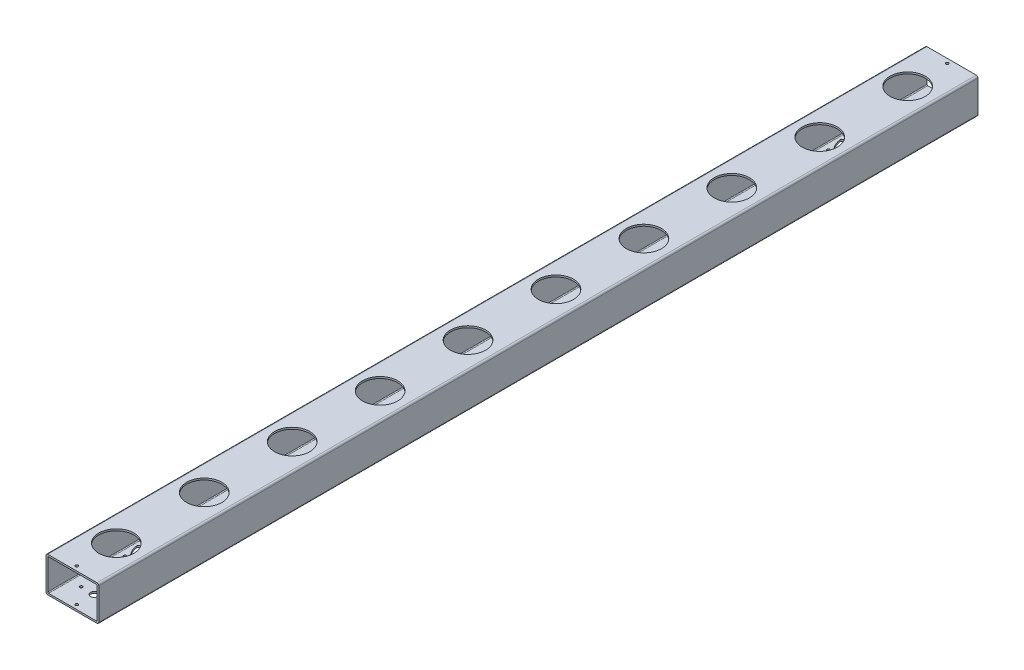
SolidWorks part; units mm, degrees
ref_plane "Plan de face" through (0, 0, 0) normal (0, 0, 1) x (1, 0, 0)
ref_plane "Plan de dessus" through (0, 0, 0) normal (0, 1, 0) x (1, 0, 0)
ref_plane "Plan de droite" through (0, 0, 0) normal (1, 0, 0) x (0, 0, -1)
sketch "Esquisse1" plane through (0, 0, 0) normal (0, 0, 1) x (1, 0, 0)
  line L0 (2, 2) -> (58, 2)
  line L1 (0, 0) -> (60, 0)
  line L2 (0, 0) -> (0, 40)
  line L3 (0, 40) -> (60, 40)
  line L4 (60, 0) -> (60, 40)
  line L5 (58, 2) -> (58, 38)
  line L6 (2, 38) -> (58, 38)
  line L7 (2, 2) -> (2, 38)
  dimension "D1" = 60
  dimension "D2" = 40
  dimension "D3" = 2
extrude "Boss.-Extru.1" add sketch "Esquisse1" along normal blind 1000
fillet "Congé1" radius 1 4 edges at (58, 2, 500) (58, 38, 500) (2, 38, 500) (2, 2, 500)
fillet "Congé2" radius 2 4 edges at (60, 0, 500) (0, 0, 500) (60, 40, 500) (0, 40, 500)
sketch "Esquisse2" plane through (0, 40, 0) normal (0, 1, 0) x (1, 0, 0)
  line L0 (30, 0) -> (30, -50) construction
  line L1 (58, 0) -> (2, 0) construction
  circle A0 centre (30, -50) radius 20
  circle A1 centre (30, -150) radius 20
  circle A2 centre (30, -250) radius 20
  circle A3 centre (30, -350) radius 20
  circle A4 centre (30, -450) radius 20
  circle A5 centre (30, -550) radius 20
  circle A6 centre (30, -650) radius 20
  circle A7 centre (30, -750) radius 20
  circle A8 centre (30, -850) radius 20
  circle A9 centre (30, -950) radius 20
  dimension "D1" = 40
  dimension "D2" = 50
  dimension "D4" = 100
  dimension "D3" = 10
extrude "Enlèv. mat.-Extru.1" cut sketch "Esquisse2" against normal up to next
sketch "Esquisse3" plane through (0, 0, 0) normal (0, -1, 0) x (1, 0, 0)
  line L0 (30, 975) -> (30, 1000) construction
  line L1 (2, 1000) -> (58, 1000) construction
  line L2 (30, 25) -> (30, 0) construction
  line L3 (2, 0) -> (58, 0) construction
  line L4 (30, 975) -> (30, 25) construction
  circle A0 centre (30, 975) radius 4.25
  circle A1 centre (30, 25) radius 4.25
  circle A2 centre (30, 500) radius 4.25
  dimension "D2" = 8.5
  dimension "D1" = 25
extrude "Enlèv. mat.-Extru.2" cut sketch "Esquisse3" against normal up to next
sketch "Esquisse4" plane through (0, 40, 0) normal (0, 1, 0) x (1, 0, 0)
  line L0 (12.3223, -32.3223) -> (47.6777, -67.6777) construction
  line L1 (2, 0) -> (2, -1000) construction
  circle A0 centre (30, -50) radius 25 construction
  circle A1 centre (30, -50) radius 20 construction
  circle A2 centre (12.3223, -32.3223) radius 1.6
  circle A3 centre (47.6777, -67.6777) radius 1.6
  point P6 (30, -50)
  dimension "D1" = 50
  dimension "D3" = 3.2
  dimension "D2" = 45
extrude "Enlèv. mat.-Extru.3" [suppressed] cut sketch "Esquisse4" against normal up to next
sketch "Esquisse6" plane through (0, 0, 0) normal (0, -1, 0) x (-1, 0, 0)
  line L0 (-20, -400) -> (-40, -400) construction
  line L1 (0, -400) -> (-20, -400) construction
  line L3 (0, 0) -> (0, -1000) construction
  line L4 (-40, -400) -> (-60, -400) construction
  line L5 (-60, -1000) -> (-60, 0) construction
  line L6 (-30, -370) -> (-30, -400) construction
  line L7 (-30, -400) -> (-30, -430) construction
  circle A0 centre (-20, -400) radius 2.25
  circle A1 centre (-40, -400) radius 2.25
  circle A2 centre (-30, -350) radius 20 construction
  circle A3 centre (-30, -450) radius 20 construction
  dimension "D2" = 4.5
  dimension "D1" = 20
extrude "Enlèv. mat.-Extru.4" cut sketch "Esquisse6" against normal up to next
pattern_linear "Répétition linéaire1" count 3 spacing 200 along (0, 0, 1) count 2 spacing 200 along (0, 0, -1) of "Enlèv. mat.-Extru.4"
sketch "Esquisse7" plane through (0, 0, 0) normal (0, -1, 0) x (-1, 0, 0)
  line L0 (-15, -500) -> (-45, -500) construction
  line L1 (-15, -975) -> (-45, -975) construction
  line L2 (-15, -25) -> (-45, -25) construction
  circle A0 centre (-15, -25) radius 1.6
  circle A1 centre (-45, -25) radius 1.6
  circle A2 centre (-15, -500) radius 1.6
  circle A3 centre (-45, -500) radius 1.6
  circle A4 centre (-15, -975) radius 1.6
  circle A5 centre (-45, -975) radius 1.6
  point P2 (-30, -500)
  point P3 (-30, -975)
  point P7 (-30, -25)
  dimension "D1" = 3.2
  dimension "D2" = 30
extrude "Enlèv. mat.-Extru.5" cut sketch "Esquisse7" against normal up to next
pattern_linear "Répétition linéaire2" [suppressed] count 10 spacing 100
sketch "Esquisse8" plane through (0, 0, 0) normal (0, -1, 0) x (-1, 0, 0)
  circle A0 centre (-38, -55.1826) radius 1.4
  circle A1 centre (-22, -55.1826) radius 1.4
  circle A2 centre (-22, -55.1826) radius 1.25 construction
  circle A3 centre (-38, -55.1826) radius 1.25 construction
  dimension "D1" = 2.8
sketch "Esquisse9" plane through (0, 0, 0) normal (0, -1, 0) x (1, 0, 0)
  circle A1 centre (30, 950) radius 9.5306 construction
  circle A2 centre (30, 950) radius 20 construction
  circle A3 centre (22, 955.18) radius 1.1
  circle A4 centre (38, 955.18) radius 1.1
  dimension "D1" = 2.2
  dimension "D2" = 5.18
  dimension "D3" = 16
extrude "Enlèv. mat.-Extru.6" cut sketch "Esquisse9" against normal up to next
pattern_linear "Répétition linéaire3" count 10 spacing 100 along (0, 0, -1) of "Enlèv. mat.-Extru.6"
sketch "Esquisse10" plane through (0, 0, 0) normal (0, -1, 0) x (1, 0, 0)
  line L0 (2, 0) -> (58, 0) construction
  line L1 (10, 80) -> (50, 80) construction
  line L2 (10, 80) -> (10, 120) construction
  line L3 (10, 120) -> (50, 120) construction
  line L4 (50, 80) -> (50, 120) construction
  line L6 (0, 100) -> (10, 100) construction
  line L7 (0, 0) -> (0, 1000) construction
  line L8 (50, 100) -> (60, 100) construction
  line L9 (60, 1000) -> (60, 0) construction
  circle A0 centre (10, 120) radius 1.75
  circle A1 centre (50, 120) radius 1.75
  circle A2 centre (50, 80) radius 1.75
  circle A3 centre (10, 80) radius 1.75
  dimension "D2" = 3.5
  dimension "D1" = 40
  dimension "D3" = 100
extrude "Enlèv. mat.-Extru.7" cut sketch "Esquisse10" against normal up to next
pattern_linear "Répétition linéaire4" count 2 spacing 800 along (0, 0, 1) of "Enlèv. mat.-Extru.7"
sketch "Esquisse11" plane through (0, 0, 0) normal (0, -1, 0) x (1, 0, 0)
  line L1 (30, 910) -> (30, 916) construction
  line L2 (30, 918) -> (30, 924) construction
  line L3 (12.0278, 899) -> (6.0208, 899)
  line L4 (20.0501, 899) -> (14.0313, 899)
  line L6 (20.0501, 901) -> (14.0313, 901)
  line L8 (12.0278, 901) -> (6.0208, 901)
  line L9 (20.0501, 901) -> (20.0501, 899) construction
  line L10 (38.1201, 916.0644) -> (41.1236, 921.2666)
  line L11 (39.8521, 915.0644) -> (42.8556, 920.2666)
  line L12 (35.841, 908.1168) -> (38.8504, 913.3293)
  line L13 (34.1089, 909.1168) -> (37.1183, 914.3293)
  line L14 (39.8521, 884.9356) -> (42.8556, 879.7334)
  line L15 (38.1201, 883.9356) -> (41.1236, 878.7334)
  line L16 (34.1089, 890.8832) -> (37.1183, 885.6707)
  line L17 (35.841, 891.8832) -> (38.8504, 886.6707)
  arc A0 (41.1236, 921.2666) -> (42.8556, 920.2666) centre (30, 900) ccw
  arc A1 (20.0501, 899) -> (34.1089, 890.8832) centre (30, 900) ccw
  arc A2 (14.0313, 899) -> (37.1183, 885.6707) centre (30, 900) ccw
  arc A3 (12.0278, 899) -> (38.1201, 883.9356) centre (30, 900) ccw
  arc A4 (24.1103, 908.0815) -> (20.0094, 900.434) centre (30, 900) ccw construction
  arc A5 (39.8521, 884.9356) -> (39.8521, 915.0644) centre (30, 900) ccw
  arc A6 (38.8504, 886.6707) -> (38.8504, 913.3293) centre (30, 900) ccw
  arc A7 (35.841, 891.8832) -> (35.841, 908.1168) centre (30, 900) ccw
  arc A8 (38.1201, 916.0644) -> (12.0278, 901) centre (30, 900) ccw
  arc A9 (37.1183, 914.3293) -> (14.0313, 901) centre (30, 900) ccw
  arc A10 (34.1089, 909.1168) -> (20.0501, 901) centre (30, 900) ccw
  dimension "D1" = 48
  dimension "D2" = 20
  dimension "D3" = 2
  dimension "D4" = 2
  dimension "D5" = 3
extrude "Enlèv. mat.-Extru.8" cut sketch "Esquisse11" against normal up to next contours A8 L10 A0 L8 | A3 L3 A0 L15 | A5 L14 A0 L11 | L4 A2 L16 A1 | A7 L17 A6 L12 | A10 L13 A9 L6
fillet "Congé3" radius 2 24 edges at (6.0208, 1, 899) (12.0278, 1, 899) (14.0313, 1, 899) (20.0501, 1, 899) (34.1089, 1, 890.8832) (37.1183, 1, 885.6707) (38.1201, 1, 883.9356) (41.1236, 1, 878.7334) (42.8556, 1, 879.7334) (38.8504, 1, 886.6707) (39.8521, 1, 884.9356) (35.841, 1, 891.8832) (39.8521, 1, 915.0644) (42.8556, 1, 920.2666) (35.841, 1, 908.1168) (38.8504, 1, 913.3293) (34.1089, 1, 909.1168) (37.1183, 1, 914.3293) (20.0501, 1, 901) (14.0313, 1, 901) (6.0208, 1, 901) (12.0278, 1, 901) (38.1201, 1, 916.0644) (41.1236, 1, 921.2666)
pattern_linear "Répétition linéaire5" count 2 spacing 800 along (0, 0, -1) of "Enlèv. mat.-Extru.8", "Congé3"
sketch "Esquisse12" plane through (0, 0, 0) normal (0, -1, 0) x (1, 0, 0)
  line L0 (38, 755.18) -> (38, 740.18) construction
  line L1 (10, 740.18) -> (50, 740.18) construction
  line L2 (10, 740.18) -> (10, 670.18) construction
  line L3 (10, 670.18) -> (50, 670.18) construction
  line L4 (50, 740.18) -> (50, 670.18) construction
  line L5 (22, 655.18) -> (22, 670.18) construction
  line L6 (10, 705.18) -> (0, 705.18) construction
  line L7 (50, 705.18) -> (60, 705.18) construction
  line L8 (60, 1000) -> (60, 0) construction
  line L9 (0, 0) -> (0, 1000) construction
  circle A0 centre (10, 740.18) radius 1.6
  circle A1 centre (50, 740.18) radius 1.6
  circle A2 centre (50, 670.18) radius 1.6
  circle A3 centre (10, 670.18) radius 1.6
  dimension "D1" = 3.2
  dimension "D2" = 40
  dimension "D3" = 70
extrude "Enlèv. mat.-Extru.9" cut sketch "Esquisse12" against normal up to next
sketch "Esquisse13" plane through (0, 0, 0) normal (0, -1, 0) x (1, 0, 0)
  line L0 (17, 722.18) -> (0, 722.18) construction
  line L1 (17, 729.18) -> (43, 729.18)
  line L2 (17, 729.18) -> (17, 715.18)
  line L3 (17, 715.18) -> (43, 715.18)
  line L4 (43, 729.18) -> (43, 715.18)
  line L5 (0, 0) -> (0, 1000) construction
  line L6 (43, 722.18) -> (60, 722.18) construction
  line L7 (60, 1000) -> (60, 0) construction
  line L9 (30, 705.18) -> (30, 715.18) construction
  line L10 (17, 705.18) -> (30, 705.18) construction
  line L11 (30, 705.18) -> (43, 705.18) construction
  circle A0 centre (17, 705.18) radius 1.9
  circle A1 centre (30, 705.18) radius 1.9
  circle A2 centre (43, 705.18) radius 1.9
  circle A3 centre (10, 740.18) radius 1.6 construction
  dimension "D6" = 3.8
  dimension "D3" = 18
  dimension "D1" = 26
  dimension "D2" = 14
  dimension "D4" = 13
  dimension "D5" = 10
extrude "Enlèv. mat.-Extru.10" cut sketch "Esquisse13" against normal up to next
sketch "Esquisse14" plane through (0, 0, 0) normal (0, -1, 0) x (1, 0, 0)
  line L0 (30, 995) -> (30, 1000) construction
  line L1 (2, 1000) -> (58, 1000) construction
  line L2 (30, 5) -> (30, 0) construction
  line L3 (2, 0) -> (58, 0) construction
  circle A0 centre (30, 5) radius 1.6
  circle A1 centre (30, 995) radius 1.6
  dimension "D1" = 3.2
  dimension "D2" = 5
extrude "Enlèv. mat.-Extru.11" cut sketch "Esquisse14" against normal through all
sketch "Esquisse15" plane through (0, 0, 0) normal (0, -1, 0) x (1, 0, 0)
  line L4 (20, 400) -> (40, 400) construction
  line L5 (30, 425) -> (30, 400) construction
  circle A3 centre (30, 425) radius 2.5
  dimension "D3" = 5
  dimension "D4" = 25
extrude "Enlèv. mat.-Extru.12" cut sketch "Esquisse15" against normal up to next
sketch "Esquisse16" plane through (0, 0, 0) normal (0, -1, 0) x (1, 0, 0)
  line L0 (30, 962.7) -> (30, 950) construction
  line L1 (30, 950) -> (30, 937.3) construction
  line L2 (22, 955.18) -> (30, 955.18) construction
  line L3 (30, 955.18) -> (38, 955.18) construction
  circle A0 centre (30, 962.7) radius 1.65
  circle A1 centre (30, 937.3) radius 1.65
  circle A2 centre (38, 955.18) radius 1.1 construction
  point P5 (30, 950)
  dimension "D1" = 3.3
  dimension "D2" = 5.18
  dimension "D3" = 25.4
extrude "Enlèv. mat.-Extru.13" cut sketch "Esquisse16" against normal up to next
pattern_linear "Répétition linéaire6" count 10 spacing 100 along (0, 0, -1) of "Enlèv. mat.-Extru.13"
